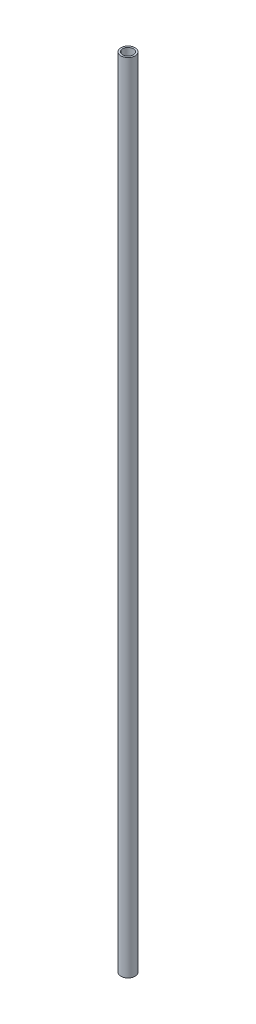
SolidWorks part; units mm, degrees
ref_plane "Front Plane" through (0, 0, 0) normal (0, 0, 1) x (1, 0, 0)
ref_plane "Top Plane" through (0, 0, 0) normal (0, 1, 0) x (1, 0, 0)
ref_plane "Right Plane" through (0, 0, 0) normal (1, 0, 0) x (0, 0, -1)
sketch "Sketch1" plane through (0, 0, 0) normal (0, 0, 1) x (1, 0, 0)
  line L0 (0, 0) -> (0, 450)
  point P6 (0, 450)
  dimension "D1" = 450
sketch "Sketch2" plane through (0, 0, 0) normal (0, 1, 0) x (1, 0, 0)
  circle A0 centre (0, 0) radius 4
  circle A1 centre (0, 0) radius 3
  dimension "D1" = 6
  dimension "D2" = 8
sweep "Sweep1" add profiles "Sketch2" path "Sketch1"
